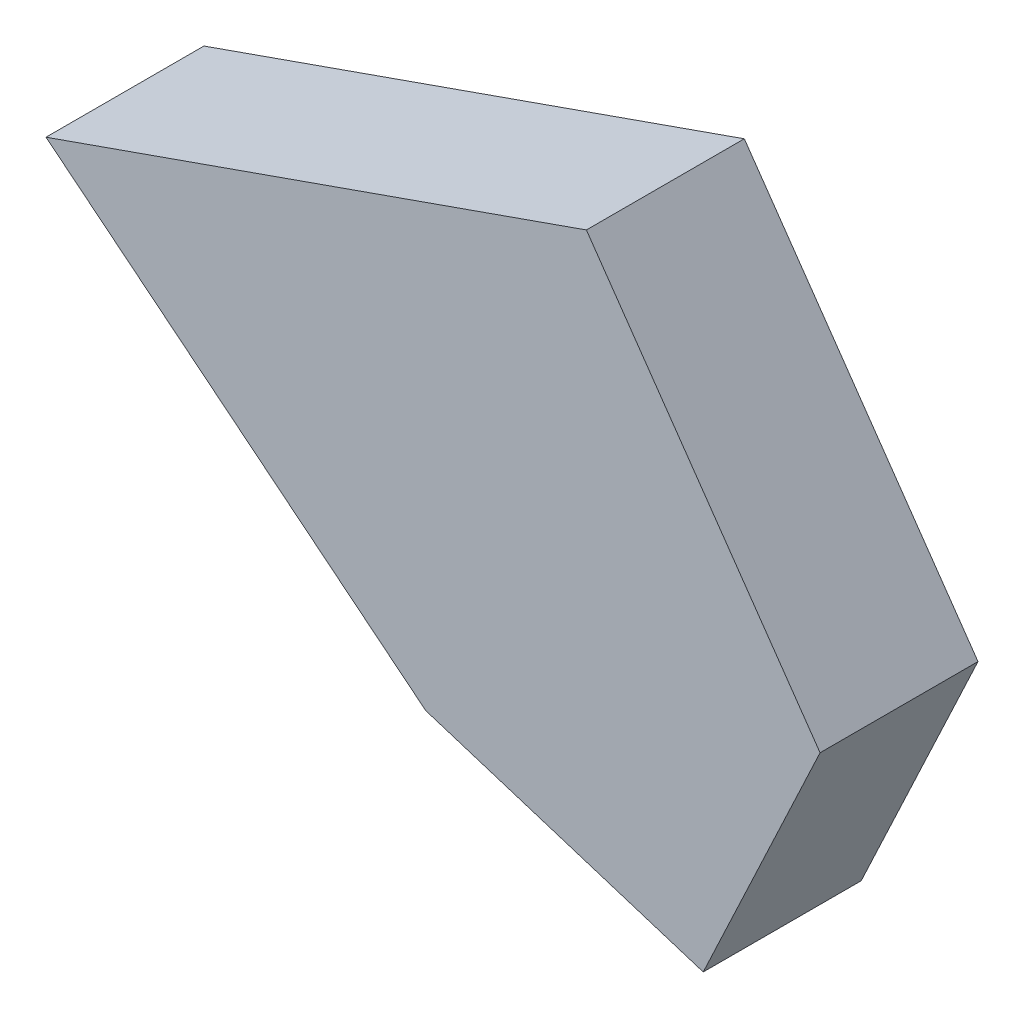
SolidWorks part; units mm, degrees
ref_plane "Front Plane" through (0, 0, 0) normal (0, 0, 1) x (1, 0, 0)
ref_plane "Top Plane" through (0, 0, 0) normal (0, 1, 0) x (1, 0, 0)
ref_plane "Right Plane" through (0, 0, 0) normal (1, 0, 0) x (0, 0, -1)
sketch "Sketch1" plane through (0, 0, 0) normal (0, 0, 1) x (1, 0, 0)
  line L0 (0, -3) -> (19, -9)
  line L1 (19, -9) -> (27, 8)
  line L2 (27, 8) -> (11, 31)
  line L3 (11, 31) -> (-26, 18)
  line L4 (-26, 18) -> (0, -3)
extrude "Boss-Extrude1" add sketch "Sketch1" along normal blind 10.813
